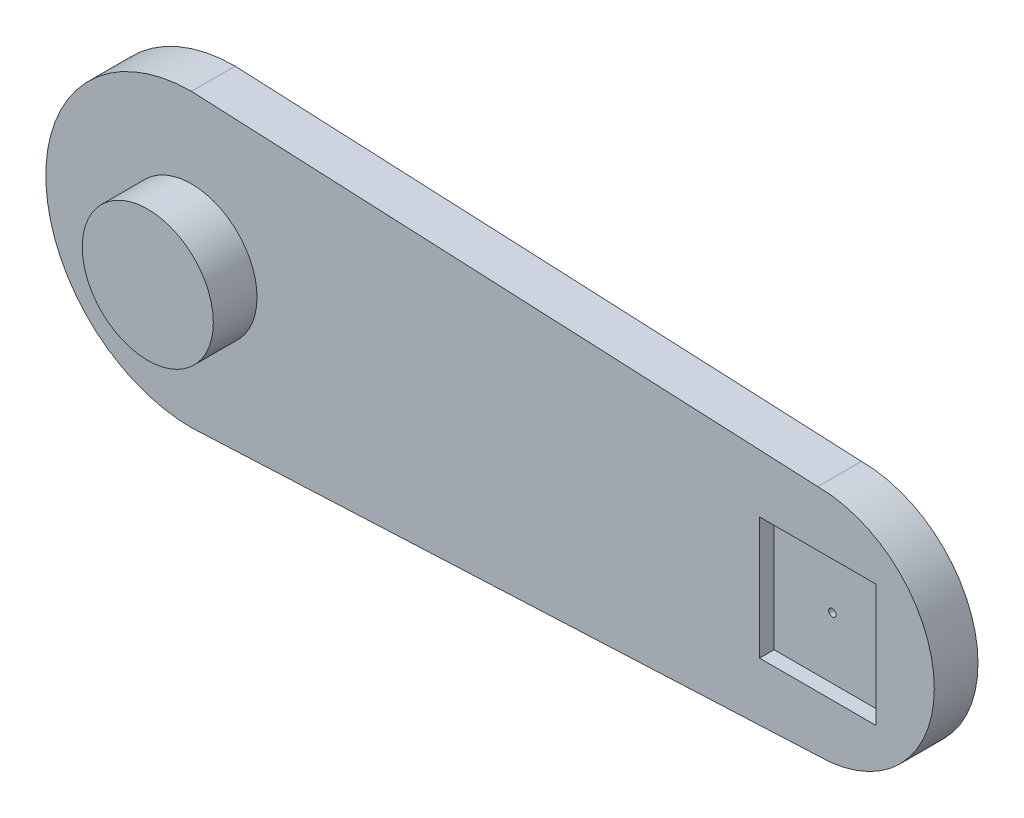
SolidWorks part; units mm, degrees
ref_plane "Alzado" through (0, 0, 0) normal (0, 0, 1) x (1, 0, 0)
ref_plane "Planta" through (0, 0, 0) normal (0, 1, 0) x (1, 0, 0)
ref_plane "Vista lateral" through (0, 0, 0) normal (1, 0, 0) x (0, 0, -1)
sketch "Croquis1" plane through (0, 0, 0) normal (0, 0, 1) x (1, 0, 0)
  line L0 (0, 0) -> (215, 0) construction
  line L1 (0, 50) -> (215, 40)
  line L2 (0, -50) -> (215, -40)
  circle A0 centre (0, 0) radius 1.25
  circle A1 centre (0, 0) radius 50
  circle A2 centre (215, 0) radius 40
  circle A3 centre (215, 0) radius 1.25
  dimension "D1" = 2.5
  dimension "D2" = 100
  dimension "D4" = 80
  dimension "D5" = 2.5
  dimension "D3" = 215
extrude "Saliente-Extruir1" add sketch "Croquis1" along normal blind 15
sketch "Croquis4" plane through (0, 0, 15) normal (0, 0, 1) x (1, 0, 0)
  circle A0 centre (0, 0) radius 22.5
  dimension "D1" = 45
extrude "Saliente-Extruir2" add sketch "Croquis4" along normal blind 15
sketch "Croquis5" plane through (0, 0, 0) normal (0, 0, -1) x (-1, 0, 0)
  circle A0 centre (0, 0) radius 11
  dimension "D1" = 22
extrude "Cortar-Extruir1" cut sketch "Croquis5" against normal blind 5
sketch "Croquis6" plane through (0, 0, 15) normal (0, 0, 1) x (1, 0, 0)
  line L1 (195, -21) -> (235, -21)
  line L2 (195, -21) -> (195, 21)
  line L3 (195, 21) -> (235, 21)
  line L4 (235, -21) -> (235, 21)
  line L5 (195, -21) -> (235, 21) construction
  line L6 (195, 21) -> (235, -21) construction
  point P0 (215, 0)
  dimension "D1" = 40
  dimension "D2" = 42
extrude "Cortar-Extruir2" cut sketch "Croquis6" against normal blind 5
